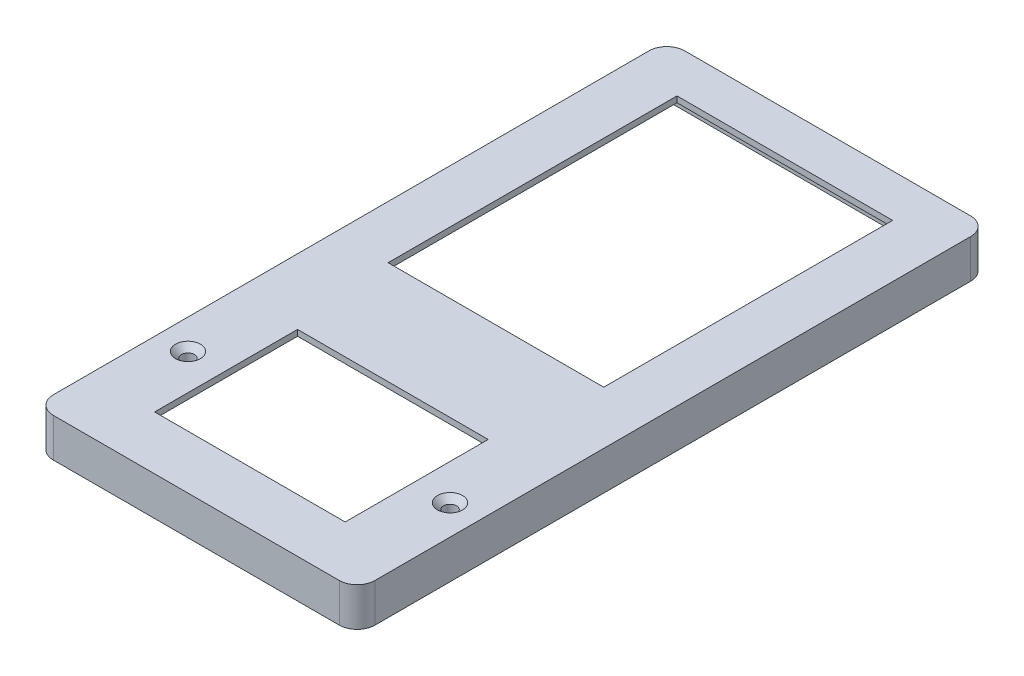
SolidWorks part; units mm, degrees
ref_plane "Front Plane" through (0, 0, 0) normal (0, 0, 1) x (1, 0, 0)
ref_plane "Top Plane" through (0, 0, 0) normal (0, 1, 0) x (1, 0, 0)
ref_plane "Right Plane" through (0, 0, 0) normal (1, 0, 0) x (0, 0, -1)
sketch "Sketch1" plane through (0, 0, 0) normal (0, 1, 0) x (1, 0, 0)
  line L0 (24.75, -50.75) -> (24.75, 50.75)
  line L1 (27, -53) -> (-27, -53)
  line L2 (27, -53) -> (27, 53)
  line L3 (27, 53) -> (-27, 53)
  line L4 (-27, -53) -> (-27, 53)
  line L5 (27, -53) -> (-27, 53) construction
  line L6 (27, 53) -> (-27, -53) construction
  line L7 (24.75, 50.75) -> (-24.75, 50.75)
  line L8 (-24.75, -50.75) -> (-24.75, 50.75)
  line L9 (24.75, -50.75) -> (-24.75, -50.75)
  point P0 (0, 0)
  dimension "D1" = 54
  dimension "D2" = 106
  dimension "D3" = 2.25
extrude "Boss-Extrude1" add sketch "Sketch1" against normal blind 5.5
sketch "Sketch2" plane through (0, 0, 0) normal (0, 1, 0) x (1, 0, 0)
  line L0 (27, 53) -> (-27, 53) construction
  line L1 (-18.1, 45.8) -> (18.1, 45.8)
  line L2 (-18.1, 45.8) -> (-18.1, -2.7)
  line L3 (-18.1, -2.7) -> (18.1, -2.7)
  line L4 (18.1, 45.8) -> (18.1, -2.7)
  line L5 (-18.1, 45.8) -> (18.1, -2.7) construction
  line L6 (-18.1, -2.7) -> (18.1, 45.8) construction
  line L7 (-27, -53) -> (27, -53) construction
  line L8 (-16, -44) -> (16, -44)
  line L9 (-16, -44) -> (-16, -20)
  line L10 (-16, -20) -> (16, -20)
  line L11 (16, -44) -> (16, -20)
  line L12 (-16, -44) -> (16, -20) construction
  line L13 (-16, -20) -> (16, -44) construction
  line L18 (-27, 53) -> (-27, -53)
  line L19 (-27, -53) -> (27, -53)
  line L20 (27, -53) -> (27, 53)
  line L21 (27, 53) -> (-27, 53)
  line L22 (-27, 53) -> (-27, -53)
  line L23 (-27, -53) -> (27, -53)
  line L24 (27, -53) -> (27, 53)
  line L25 (27, 53) -> (-27, 53)
  point P0 (0, 21.55)
  point P9 (0, -32)
  point P15 (0, -20)
  dimension "D1" = 36.2
  dimension "D2" = 48.5
  dimension "D3" = 7.2
  dimension "D4" = 33
  dimension "D5" = 9
  dimension "D6" = 32
  dimension "D7" = 0
extrude "Boss-Extrude2" add sketch "Sketch2" along normal blind 1
sketch "Sketch3" plane through (0, 0, 0) normal (0, -1, 0) x (1, 0, 0)
  line L0 (27, -53) -> (-27, -53) construction
  line L1 (21.5, 11.5715) -> (17.5, 11.5715)
  line L2 (21.5, 11.5715) -> (21.5, -48.9285)
  line L3 (21.5, -48.9285) -> (-21.5, -48.9285)
  line L4 (-21.5, 11.5715) -> (-21.5, -48.9285)
  line L5 (21.5, 11.5715) -> (-21.5, -48.9285) construction
  line L6 (21.5, -48.9285) -> (-21.5, 11.5715) construction
  line L7 (25, 15.0715) -> (25, -52.4285)
  line L8 (25, -52.4285) -> (-25, -52.4285)
  line L9 (-25, 15.0715) -> (-25, -52.4285)
  line L10 (25, 15.0715) -> (17.5, 15.0715)
  line L11 (17.5, 11.5715) -> (17.5, 15.0715)
  line L12 (-17.5, 11.5715) -> (-17.5, 15.0715)
  line L13 (-17.5, 11.5715) -> (-21.5, 11.5715)
  line L14 (21.5, 11.5715) -> (-21.5, 11.5715) construction
  line L15 (-17.5, 15.0715) -> (-25, 15.0715)
  line L16 (25, 15.0715) -> (-25, 15.0715) construction
  point P0 (0, -18.6785)
  dimension "D1" = 60.5
  dimension "D2" = 43
  dimension "D3" = 4.0715
  dimension "D5" = 4
  dimension "D6" = 4
  dimension "D4" = 3.5
extrude "Boss-Extrude3" add sketch "Sketch3" along normal blind 2
sketch "Sketch4" plane through (0, 0, 0) normal (0, -1, 0) x (1, 0, 0)
  line L0 (-27, -53) -> (-27, 53) construction
  line L1 (-27, 53) -> (27, 53) construction
  circle A0 centre (-22, 32.4) radius 3
  dimension "D3" = 6
  dimension "D1" = 5
  dimension "D2" = 20.6
extrude "Boss-Extrude4" add sketch "Sketch4" along normal blind 2
sketch "Sketch5" plane through (0, 0, 0) normal (0, -1, 0) x (1, 0, 0)
  circle A0 centre (-22, 32.4) radius 1.1
  dimension "D1" = 2.2
extrude "Cut-Extrude1" cut sketch "Sketch5" along normal through all both and the other way through all
mirror "Mirror1" about plane through (0, 0, 0) normal (1, 0, 0) of "Cut-Extrude1", "Boss-Extrude4"
fillet "Fillet1" radius 3 4 edges at (-27, -2.25, -53) (27, -2.25, -53) (27, -2.25, 53) (-27, -2.25, 53)
chamfer "Chamfer1" distance 1 angle 45 2 edges at (22, 1, 31.3) (-22, 1, 31.3)
sketch "Sketch6" plane through (0, -5.5, 0) normal (0, -1, 0) x (1, 0, 0)
  line L1 (-24.75, 50.75) -> (24.75, 50.75)
  line L2 (-24.75, 50.75) -> (-24.75, 51.75)
  line L3 (-24.75, 51.75) -> (24.75, 51.75)
  line L4 (24.75, 50.75) -> (24.75, 51.75)
  dimension "D1" = 1
extrude "Cut-Extrude2" cut sketch "Sketch6" against normal blind 2
